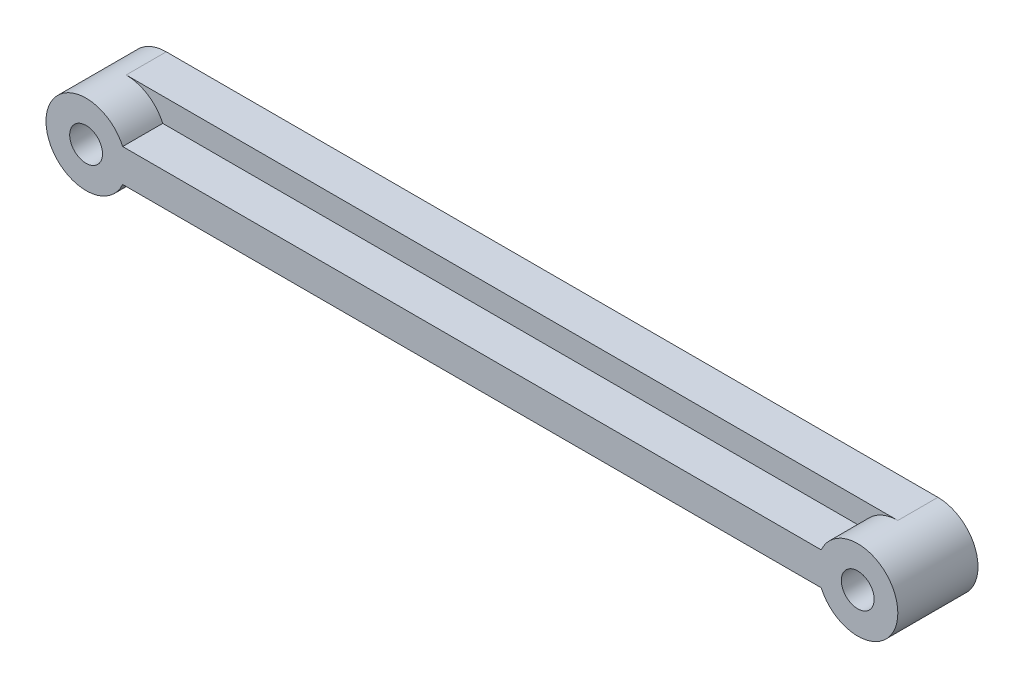
SolidWorks part; units mm, degrees
ref_plane "前视基准面" through (0, 0, 0) normal (0, 0, 1) x (1, 0, 0)
ref_plane "上视基准面" through (0, 0, 0) normal (0, 1, 0) x (1, 0, 0)
ref_plane "右视基准面" through (0, 0, 0) normal (1, 0, 0) x (0, 0, -1)
other "Configuration Table"
sketch "草图1" plane through (0, 0, 0) normal (0, 0, 1) x (1, 0, 0)
  line L2 (-45.8845, 2) -> (-7.3845, 2)
  line L3 (-45.8845, -2) -> (-7.3845, -2)
  circle A0 centre (-45.8845, 0) radius 0.8191
  circle A1 centre (-7.3845, 0) radius 0.8191
  arc A2 (-45.8845, 2) -> (-45.8845, -2) centre (-45.8845, 0) ccw
  arc A3 (-7.3845, -2) -> (-7.3845, 2) centre (-7.3845, 0) ccw
  dimension "D1" = 38.5
extrude "凸台-拉伸1" add sketch "草图1" against normal blind 2
sketch "草图2" plane through (0, 0, 0) normal (0, 0, 1) x (1, 0, 0)
  line L0 (-44.0599, 0.8191) -> (-9.2091, 0.8191)
  line L1 (-44.0599, -0.8191) -> (-9.2091, -0.8191)
  circle A0 centre (-45.8845, 0) radius 0.8191
  arc A1 (-44.0599, 0.8191) -> (-44.0599, -0.8191) centre (-45.8845, 0) ccw
  circle A2 centre (-7.3845, 0) radius 0.8191
  arc A3 (-9.2091, -0.8191) -> (-9.2091, 0.8191) centre (-7.3845, 0) ccw
extrude "凸台-拉伸2" add sketch "草图2" along normal blind 2
